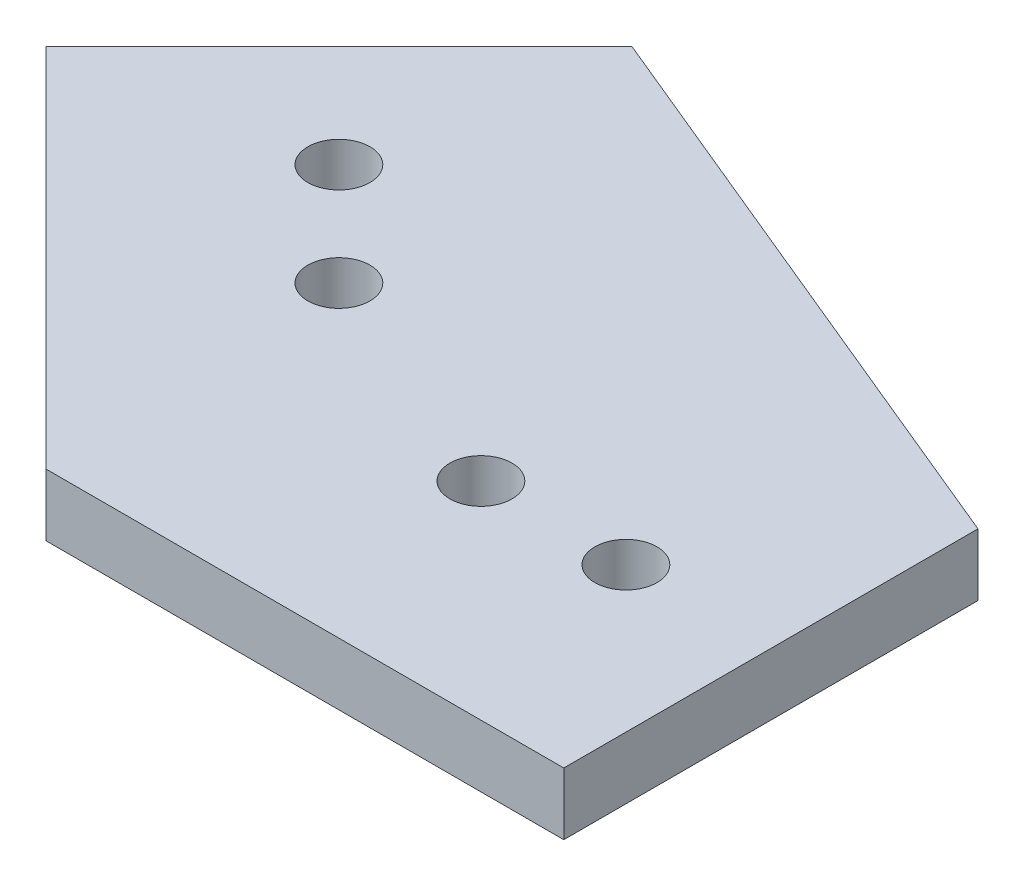
SolidWorks part; units mm, degrees
ref_plane "Front Plane" through (0, 0, 0) normal (0, 0, 1) x (1, 0, 0)
ref_plane "Top Plane" through (0, 0, 0) normal (0, 1, 0) x (1, 0, 0)
ref_plane "Right Plane" through (0, 0, 0) normal (1, 0, 0) x (0, 0, -1)
sketch "Sketch1" plane through (0, 0, 0) normal (0, 1, 0) x (1, 0, 0)
  line L0 (0, 0) -> (25, 0)
  line L1 (0, 0) -> (27.4461, 66.2608) construction
  line L2 (0, 0) -> (-17.6777, 17.6777)
  line L3 (25, 0) -> (25, 20)
  line L4 (-17.6777, 17.6777) -> (-3.5355, 31.8198)
  line L5 (25, 20) -> (-3.5355, 31.8198)
  line L6 (25, 10) -> (4.1421, 10) construction
  line L7 (-10.6066, 24.7487) -> (4.1421, 10) construction
  circle A0 centre (18, 10) radius 1.5
  circle A1 centre (11, 10) radius 1.5
  circle A2 centre (-5.6569, 19.799) radius 1.5
  circle A3 centre (-0.7071, 14.8492) radius 1.5
  dimension "D4" = 3
  dimension "D5" = 3
  dimension "D6" = 7
  dimension "D7" = 7
  dimension "D1" = 67.5
  dimension "D2" = 20
  dimension "D3" = 25
extrude "Boss-Extrude1" add sketch "Sketch1" along normal blind 3
